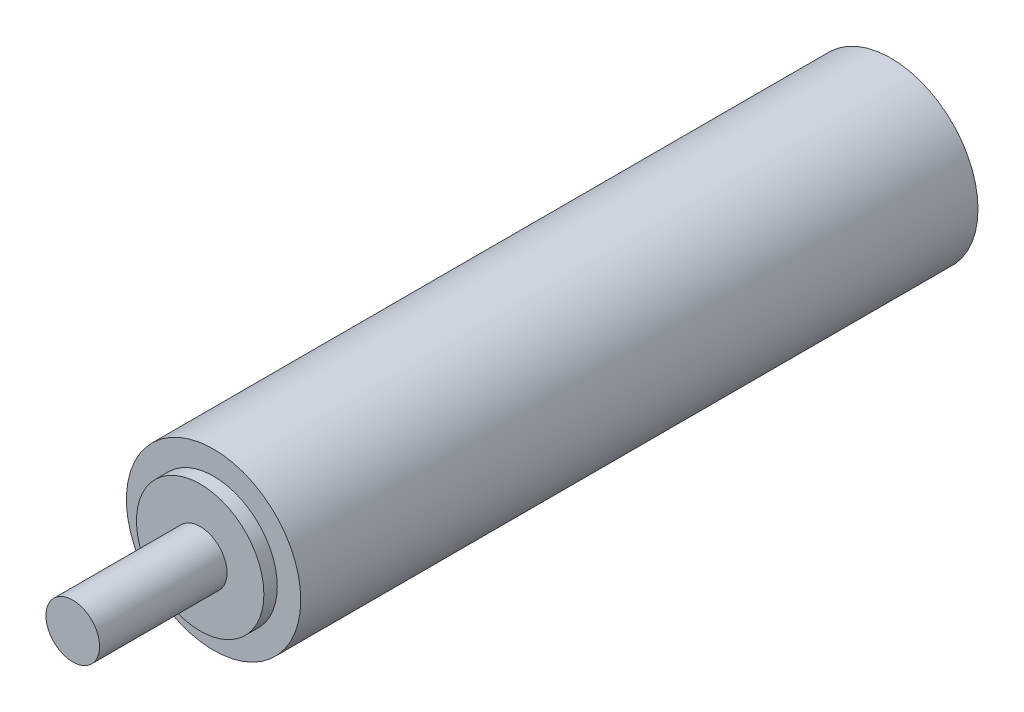
SolidWorks part; units mm, degrees
ref_plane "Front Plane" through (0, 0, 0) normal (0, 0, 1) x (1, 0, 0)
ref_plane "Top Plane" through (0, 0, 0) normal (0, 1, 0) x (1, 0, 0)
ref_plane "Right Plane" through (0, 0, 0) normal (1, 0, 0) x (0, 0, -1)
sketch "Sketch1" plane through (0, 0, 0) normal (0, 0, 1) x (1, 0, 0)
  circle A0 centre (0, 0) radius 13
  dimension "D1" = 26
extrude "Boss-Extrude1" add sketch "Sketch1" along normal blind 101
sketch "Sketch2" plane through (0, 0, 101) normal (0, 0, 1) x (1, 0, 0)
  circle A0 centre (0, 0) radius 9.5
  dimension "D1" = 19
extrude "Boss-Extrude2" add sketch "Sketch2" along normal blind 2
sketch "Sketch3" plane through (0, 0, 103) normal (0, 0, 1) x (1, 0, 0)
  circle A0 centre (0, 0) radius 4
  dimension "D1" = 8
extrude "Boss-Extrude3" add sketch "Sketch3" along normal blind 19
